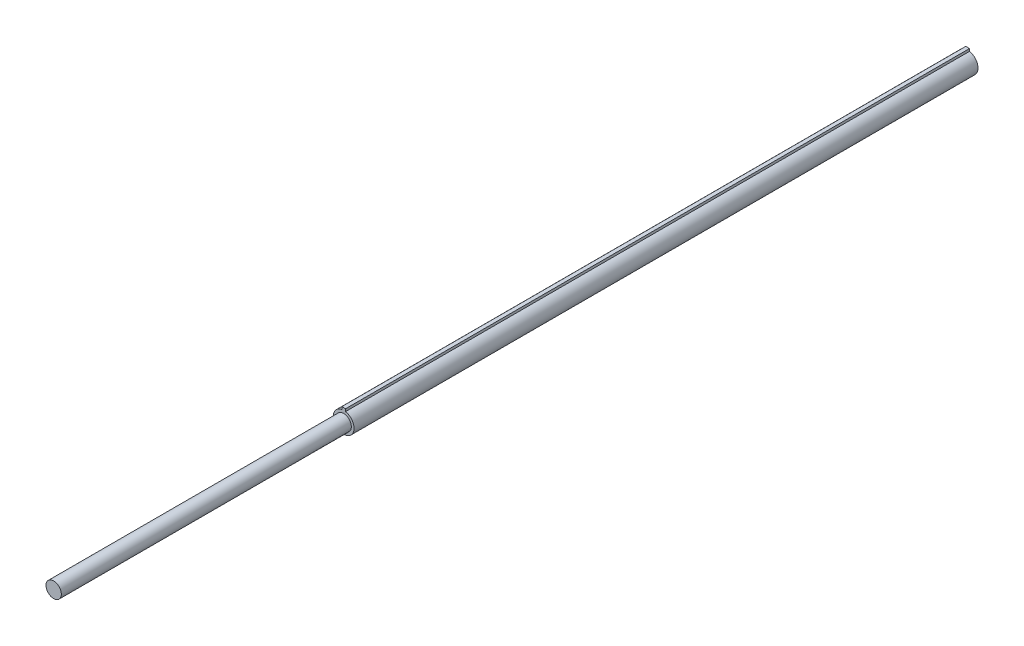
SolidWorks part; units mm, degrees
ref_plane "Alzado" through (0, 0, 0) normal (0, 0, 1) x (1, 0, 0)
ref_plane "Planta" through (0, 0, 0) normal (0, 1, 0) x (1, 0, 0)
ref_plane "Vista lateral" through (0, 0, 0) normal (1, 0, 0) x (0, 0, -1)
sketch "Croquis1" plane through (0, 0, 0) normal (0, 0, 1) x (1, 0, 0)
  line L0 (-77.6276, 118.8395) -> (-77.6276, 121.3395) construction
  line L3 (-78.0776, 121.2987) -> (-78.0776, 121.8987)
  line L4 (-78.0776, 121.8987) -> (-77.1776, 121.8987)
  line L5 (-77.1776, 121.2987) -> (-77.1776, 121.8987)
  arc A0 (-78.0776, 121.2987) -> (-77.1776, 121.2987) centre (-77.6276, 118.8395) ccw
  dimension "D1" = 5
  dimension "D2" = 0.9
  dimension "D3" = 0.6
extrude "Saliente-Extruir1" add sketch "Croquis1" along normal blind 150.6
sketch "Croquis2" plane through (0, 0, 150.6) normal (0, 0, 1) x (1, 0, 0)
  circle A0 centre (-77.6276, 118.8395) radius 1.85
  dimension "D1" = 3.7
extrude "Saliente-Extruir2" add sketch "Croquis2" along normal blind 70
